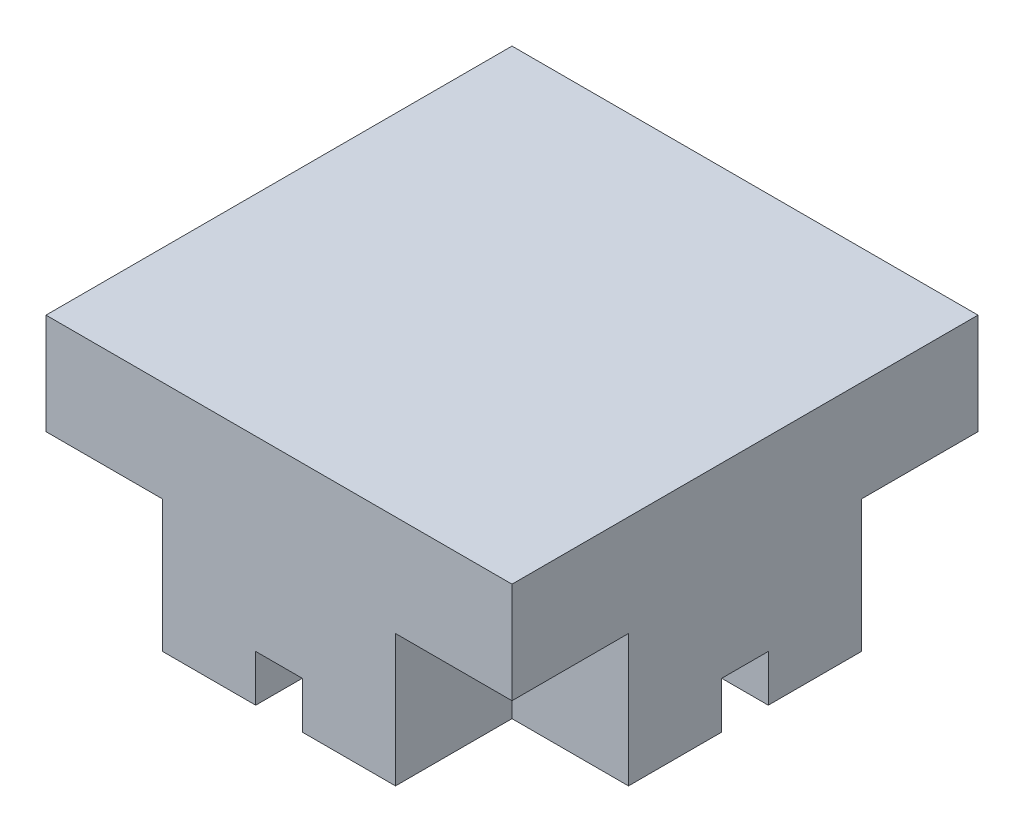
SolidWorks part; units mm, degrees
material "Normal-weight Concrete"
ref_plane "Front Plane" through (0, 0, 0) normal (0, 0, 1) x (1, 0, 0)
ref_plane "Top Plane" through (0, 0, 0) normal (0, 1, 0) x (1, 0, 0)
ref_plane "Right Plane" through (0, 0, 0) normal (1, 0, 0) x (0, 0, -1)
other "Center of Mass"
sketch "Sketch1" plane through (0, 0, 0) normal (0, 1, 0) x (1, 0, 0)
  line L1 (-1500, -1500) -> (1500, -1500)
  line L2 (-1500, -1500) -> (-1500, 1500)
  line L3 (-1500, 1500) -> (1500, 1500)
  line L4 (1500, -1500) -> (1500, 1500)
  line L5 (0, 1500) -> (0, -1500) construction
  line L6 (-1500, 0) -> (1500, 0) construction
  point P0 (0, 0)
  dimension "D1" = 3000
extrude "Boss-Extrude1" add sketch "Sketch1" along normal blind 1500
sketch "Sketch2" plane through (0, 0, 0) normal (0, -1, 0) x (1, 0, 0)
  line L1 (-1500, 1500) -> (-750, 1500)
  line L2 (-1500, 1500) -> (-1500, 750)
  line L3 (-1500, 750) -> (-750, 750)
  line L4 (-750, 1500) -> (-750, 750)
  line L5 (1500, 1500) -> (750, 1500)
  line L6 (1500, 1500) -> (1500, 750)
  line L7 (1500, 750) -> (750, 750)
  line L8 (750, 1500) -> (750, 750)
  line L9 (1500, -1500) -> (750, -1500)
  line L10 (1500, -1500) -> (1500, -750)
  line L11 (1500, -750) -> (750, -750)
  line L12 (750, -1500) -> (750, -750)
  line L13 (-1500, -1500) -> (-750, -1500)
  line L14 (-1500, -1500) -> (-1500, -750)
  line L15 (-1500, -750) -> (-750, -750)
  line L16 (-750, -1500) -> (-750, -750)
  dimension "D1" = 1500
  dimension "D2" = 1500
extrude "Cut-Extrude1" cut sketch "Sketch2" against normal blind 850
sketch "Sketch4" plane through (0, 0, 0) normal (0, -1, 0) x (1, 0, 0)
  line L0 (-750, 1500) -> (750, 1500) construction
  line L1 (-150, 1500) -> (150, 1500)
  line L2 (-150, 1500) -> (-150, 1200)
  line L3 (-150, 1200) -> (150, 1200)
  line L4 (150, 1500) -> (150, 1200)
  line L5 (1500, 750) -> (1500, -750) construction
  line L6 (1500, 150) -> (1200, 150)
  line L7 (1500, 150) -> (1500, -150)
  line L8 (1500, -150) -> (1200, -150)
  line L9 (1200, 150) -> (1200, -150)
  line L10 (750, -1500) -> (-750, -1500) construction
  line L11 (150, -1500) -> (-150, -1500)
  line L12 (150, -1500) -> (150, -1200)
  line L13 (150, -1200) -> (-150, -1200)
  line L14 (-150, -1500) -> (-150, -1200)
  line L15 (-1500, -750) -> (-1500, 750) construction
  line L16 (-1500, 150) -> (-1200, 150)
  line L17 (-1500, 150) -> (-1500, -150)
  line L18 (-1500, -150) -> (-1200, -150)
  line L19 (-1200, 150) -> (-1200, -150)
  line L22 (-750, 1200) -> (-150, 1200) construction
  line L23 (-750, 750) -> (-750, 1500) construction
  line L24 (150, 1200) -> (750, 1200) construction
  line L25 (750, 1500) -> (750, 750) construction
  line L26 (1200, 750) -> (1200, 150) construction
  line L27 (750, 750) -> (1500, 750) construction
  line L28 (1200, -150) -> (1200, -750) construction
  line L29 (1500, -750) -> (750, -750) construction
  line L30 (150, -1200) -> (750, -1200) construction
  line L31 (750, -750) -> (750, -1500) construction
  line L32 (-150, -1200) -> (-750, -1200) construction
  line L33 (-750, -1500) -> (-750, -750) construction
  line L34 (-1200, -150) -> (-1200, -750) construction
  line L35 (-750, -750) -> (-1500, -750) construction
  line L36 (-1200, 150) -> (-1200, 750) construction
  line L37 (-1500, 750) -> (-750, 750) construction
  dimension "D1" = 300
extrude "Cut-Extrude2" cut sketch "Sketch4" against normal blind 300
